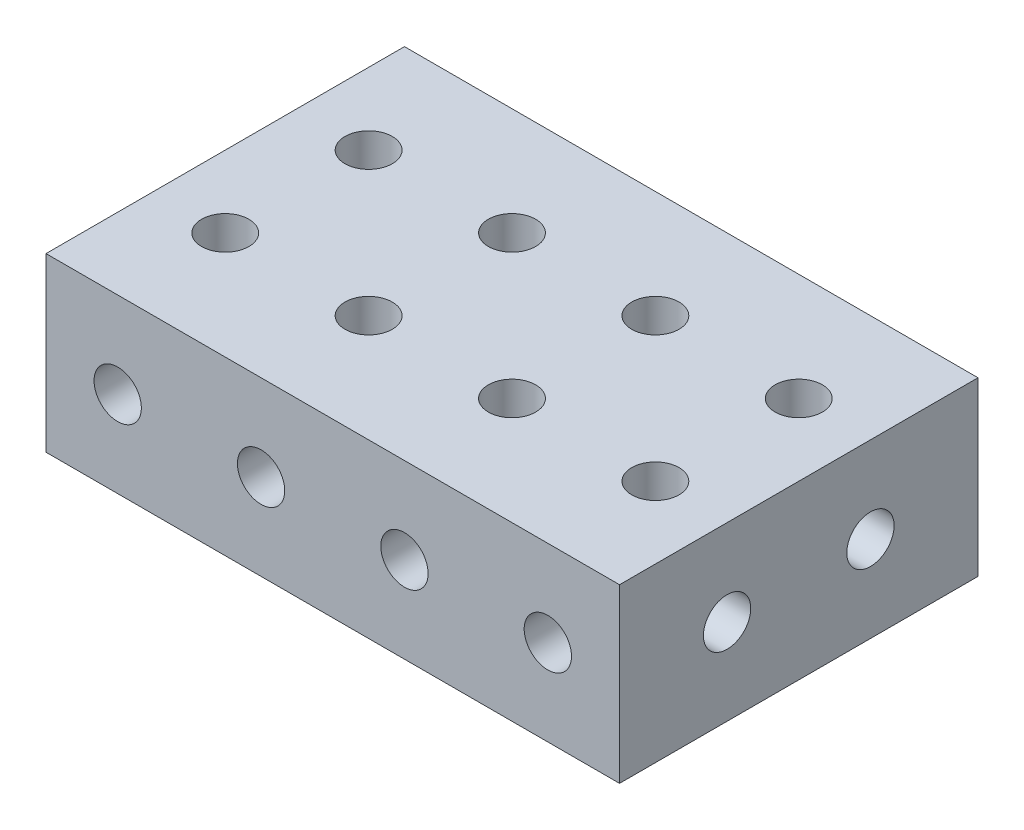
SolidWorks part; units mm, degrees
ref_plane "Plan de face" through (0, 0, 0) normal (0, 0, 1) x (1, 0, 0)
ref_plane "Plan de dessus" through (0, 0, 0) normal (0, 1, 0) x (1, 0, 0)
ref_plane "Plan de droite" through (0, 0, 0) normal (1, 0, 0) x (0, 0, -1)
sketch "Esquisse1" plane through (0, 0, 0) normal (1, 0, 0) x (0, 0, -1)
  line L1 (0, 0) -> (25, 0)
  line L2 (0, 0) -> (0, 12)
  line L3 (0, 12) -> (25, 12)
  line L4 (25, 0) -> (25, 12)
  dimension "D1" = 25
  dimension "D2" = 12
extrude "Boss.-Extru.1" add sketch "Esquisse1" along normal blind 40
sketch "Esquisse2" plane through (0, 12, 0) normal (0, 1, 0) x (1, 0, 0)
  line L0 (0, 17.5) -> (40, 17.5) construction
  line L1 (0, 25) -> (0, 0) construction
  line L2 (40, 25) -> (40, 0) construction
  line L3 (0, 12.5) -> (40, 12.5) construction
  line L4 (40, 12.5) -> (40, 7.5) construction
  line L5 (40, 7.5) -> (0, 7.5) construction
  circle A0 centre (5, 17.5) radius 1.65
  circle A1 centre (15, 17.5) radius 1.65
  circle A2 centre (25, 17.5) radius 1.65
  circle A3 centre (35, 17.5) radius 1.65
  circle A4 centre (5, 7.5) radius 1.65
  circle A5 centre (15, 7.5) radius 1.65
  circle A6 centre (35, 7.5) radius 1.65
  circle A7 centre (25, 7.5) radius 1.65
  dimension "D4" = 3.3
  dimension "D7" = 5
  dimension "D10" = 10
  dimension "D1" = 5
  dimension "D2" = 10
  dimension "D3" = 10
  dimension "D5" = 10
  dimension "D6" = 10
  dimension "D8" = 10
  dimension "D9" = 10
extrude "Enlèv. mat.-Extru.1" cut sketch "Esquisse2" against normal through all
sketch "Esquisse3" plane through (0, 0, 0) normal (0, 0, 1) x (1, 0, 0)
  line L0 (0, 6) -> (40, 6) construction
  line L1 (0, 12) -> (0, 0) construction
  line L2 (40, 12) -> (40, 0) construction
  circle A0 centre (5, 6) radius 1.65
  circle A1 centre (15, 6) radius 1.65
  circle A2 centre (25, 6) radius 1.65
  circle A3 centre (35, 6) radius 1.65
  dimension "D4" = 3.3
  dimension "D1" = 5
  dimension "D2" = 10
  dimension "D3" = 10
  dimension "D5" = 10
extrude "Enlèv. mat.-Extru.2" cut sketch "Esquisse3" against normal blind 40
sketch "Esquisse4" plane through (40, 0, 0) normal (1, 0, 0) x (0, 0, -1)
  line L0 (0, 6) -> (25, 6) construction
  line L1 (0, 12) -> (0, 0) construction
  line L2 (25, 0) -> (25, 12) construction
  line L3 (12.5, 12) -> (12.5, 0) construction
  line L4 (25, 12) -> (0, 12) construction
  line L5 (0, 0) -> (25, 0) construction
  line L6 (17.5, 0) -> (17.5, 12) construction
  line L7 (7.5, 12) -> (7.5, 0) construction
  circle A0 centre (17.5, 6) radius 1.65
  circle A1 centre (7.5, 6) radius 1.65
  dimension "D1" = 3.3
  dimension "D2" = 10
extrude "Enlèv. mat.-Extru.3" cut sketch "Esquisse4" against normal blind 40
